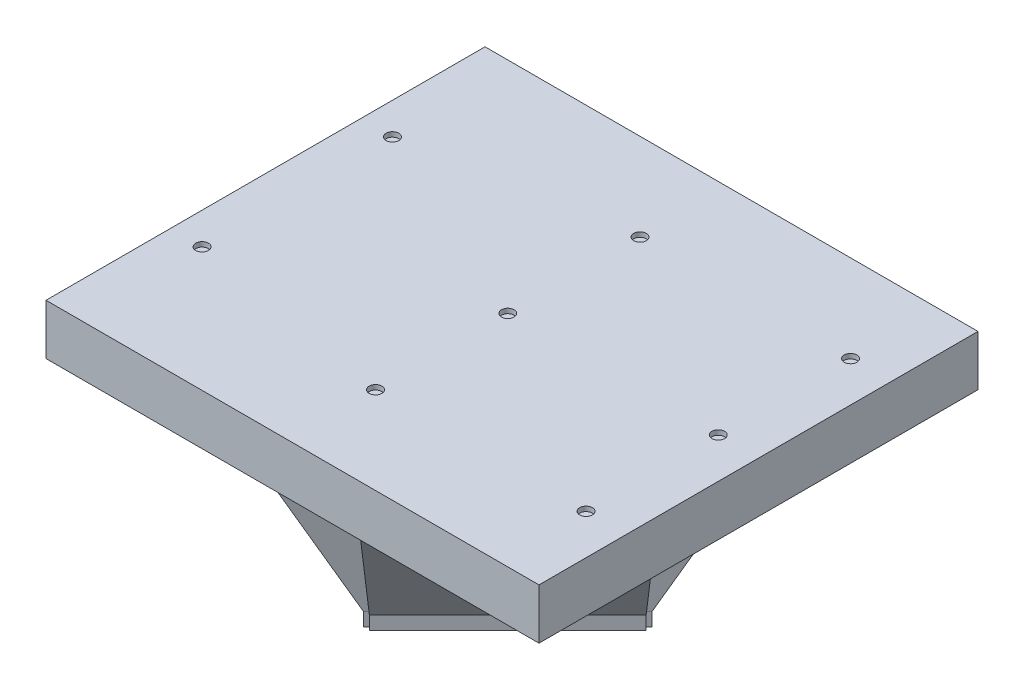
SolidWorks part; units mm, degrees
ref_plane "Front Plane" through (0, 0, 0) normal (0, 0, 1) x (1, 0, 0)
ref_plane "Top Plane" through (0, 0, 0) normal (0, 1, 0) x (1, 0, 0)
ref_plane "Right Plane" through (0, 0, 0) normal (1, 0, 0) x (0, 0, -1)
sketch "Sketch1" plane through (0, 0, 0) normal (0, 1, 0) x (1, 0, 0)
  line L1 (-46.6, 41.5) -> (46.6, 41.5)
  line L2 (-46.6, 41.5) -> (-46.6, -41.5)
  line L3 (-46.6, -41.5) -> (46.6, -41.5)
  line L4 (46.6, 41.5) -> (46.6, -41.5)
  line L5 (-46.6, 41.5) -> (46.6, -41.5) construction
  line L6 (-46.6, -41.5) -> (46.6, 41.5) construction
  point P0 (0, 0)
  dimension "D1" = 83
  dimension "D2" = 93.2
extrude "Boss-Extrude1" add sketch "Sketch1" against normal blind 9.55
sketch "Sketch2" plane through (0, -9.55, 0) normal (0, -1, 0) x (1, 0, 0)
  line L0 (-32.6387, 16.2823) -> (-17.0823, 31.8387) construction
  line L8 (-32.6387, 16.2823) -> (-17.0823, 31.8387) construction
  line L9 (-29.6334, 0.5492) -> (-37.942, 8.8577) construction
  line L10 (-29.6334, 0.5492) -> (-37.942, 8.8577) construction
  line L11 (-9.6577, 37.142) -> (-1.3492, 28.8334) construction
  line L12 (-9.6577, 37.142) -> (-1.3492, 28.8334) construction
  line L13 (15.4823, 31.8387) -> (31.0387, 16.2823) construction
  line L14 (15.4823, 31.8387) -> (31.0387, 16.2823) construction
  line L15 (-0.2508, 28.8334) -> (8.0577, 37.142) construction
  line L16 (-0.2508, 28.8334) -> (8.0577, 37.142) construction
  line L18 (36.342, 8.8577) -> (28.0334, 0.5492) construction
  line L19 (46.6, -41.5) -> (-46.6, 41.5) construction
  line L20 (36.342, 8.8577) -> (28.0334, 0.5492) construction
  line L21 (46.6, 41.5) -> (-46.6, -41.5) construction
  line L40 (31.0387, -16.2823) -> (15.4823, -31.8387) construction
  line L41 (31.0387, -16.2823) -> (15.4823, -31.8387) construction
  line L42 (28.0334, -0.5492) -> (36.342, -8.8577) construction
  line L43 (28.0334, -0.5492) -> (36.342, -8.8577) construction
  line L44 (8.0577, -37.142) -> (-0.2508, -28.8334) construction
  line L45 (8.0577, -37.142) -> (-0.2508, -28.8334) construction
  line L46 (-17.0823, -31.8387) -> (-32.6387, -16.2823) construction
  line L47 (-17.0823, -31.8387) -> (-32.6387, -16.2823) construction
  line L48 (-1.3492, -28.8334) -> (-9.6577, -37.142) construction
  line L49 (-1.3492, -28.8334) -> (-9.6577, -37.142) construction
  line L50 (-37.942, -8.8577) -> (-29.6334, -0.5492) construction
  line L51 (-37.942, -8.8577) -> (-29.6334, -0.5492) construction
  line L76 (-10.7183, -38.2026) -> (-0.8, -28.2843)
  line L77 (-0.8, -28.2843) -> (9.1183, -38.2026)
  line L78 (9.1183, -38.2026) -> (37.4026, -9.9183)
  line L79 (37.4026, -9.9183) -> (27.4843, 0)
  line L80 (27.4843, 0) -> (37.4026, 9.9183)
  line L81 (37.4026, 9.9183) -> (9.1183, 38.2026)
  line L82 (9.1183, 38.2026) -> (-0.8, 28.2843)
  line L83 (-0.8, 28.2843) -> (-10.7183, 38.2026)
  line L84 (-39.0026, 9.9183) -> (-10.7183, 38.2026)
  line L85 (-39.0026, 9.9183) -> (-29.0843, 0)
  line L86 (-29.0843, 0) -> (-39.0026, -9.9183)
  line L87 (-39.0026, -9.9183) -> (-10.7183, -38.2026)
ref_plane "Plane1" through (0, -35.75, 0) normal (0, -1, 0) x (-1, 0, 0)
sketch "Sketch3" plane through (0, -35.75, 0) normal (0, -1, 0) x (-1, 0, 0)
  line L0 (0.2508, 28.8334) -> (-28.0334, 0.5492) construction
  line L2 (1.3492, -28.8334) -> (29.6334, -0.5492) construction
  line L4 (-28.0334, -0.5492) -> (0.2508, -28.8334) construction
  line L5 (1.3492, 28.8334) -> (29.6334, 0.5492) construction
  line L6 (29.6334, -0.5492) -> (29.0843, 0) construction
  line L7 (29.0843, 0) -> (29.6334, 0.5492) construction
  line L8 (1.3492, 28.8334) -> (0.8, 28.2843) construction
  line L9 (0.8, 28.2843) -> (0.2508, 28.8334) construction
  line L10 (-28.0334, 0.5492) -> (-27.4843, 0) construction
  line L11 (-27.4843, 0) -> (-28.0334, -0.5492) construction
  line L12 (1.3492, -28.8334) -> (0.8, -28.2843) construction
  line L13 (0.8, -28.2843) -> (0.2508, -28.8334) construction
  line L14 (0.2508, 26.7121) -> (-25.9121, 0.5492)
  line L15 (-25.9121, 0.5492) -> (-25.363, 0)
  line L16 (-25.363, 0) -> (-25.9121, -0.5492)
  line L17 (-25.9121, -0.5492) -> (0.2508, -26.7121)
  line L18 (0.8, -26.163) -> (0.2508, -26.7121)
  line L19 (1.3492, -26.7121) -> (0.8, -26.163)
  line L20 (1.3492, -26.7121) -> (27.5121, -0.5492)
  line L21 (27.5121, -0.5492) -> (26.963, 0)
  line L22 (26.963, 0) -> (27.5121, 0.5492)
  line L23 (1.3492, 26.7121) -> (27.5121, 0.5492)
  line L24 (1.3492, 26.7121) -> (0.8, 26.163)
  line L25 (0.8, 26.163) -> (0.2508, 26.7121)
  dimension "D1" = 1.5
loft "Loft3" add profiles "Sketch3", "Sketch2"
sketch "Sketch5" plane through (0, -35.75, 0) normal (0, -1, 0) x (1, 0, 0)
  line L12 (-0.8, -26.163) -> (-0.2508, -26.7121)
  line L13 (-0.2508, -26.7121) -> (25.9121, -0.5492)
  line L14 (25.9121, -0.5492) -> (25.363, 0)
  line L15 (25.363, 0) -> (25.9121, 0.5492)
  line L16 (25.9121, 0.5492) -> (-0.2508, 26.7121)
  line L17 (-0.2508, 26.7121) -> (-0.8, 26.163)
  line L18 (-0.8, 26.163) -> (-1.3492, 26.7121)
  line L19 (-1.3492, 26.7121) -> (-27.5121, 0.5492)
  line L20 (-27.5121, 0.5492) -> (-26.963, 0)
  line L21 (-26.963, 0) -> (-27.5121, -0.5492)
  line L22 (-27.5121, -0.5492) -> (-1.3492, -26.7121)
  line L23 (-1.3492, -26.7121) -> (-0.8, -26.163)
  line L24 (-0.8, -26.163) -> (-0.2508, -26.7121)
  line L25 (-0.2508, -26.7121) -> (25.9121, -0.5492)
  line L26 (25.9121, -0.5492) -> (25.363, 0)
  line L27 (25.363, 0) -> (25.9121, 0.5492)
  line L28 (25.9121, 0.5492) -> (-0.2508, 26.7121)
  line L29 (-0.2508, 26.7121) -> (-0.8, 26.163)
  line L30 (-0.8, 26.163) -> (-1.3492, 26.7121)
  line L31 (-1.3492, 26.7121) -> (-27.5121, 0.5492)
  line L32 (-27.5121, 0.5492) -> (-26.963, 0)
  line L33 (-26.963, 0) -> (-27.5121, -0.5492)
  line L34 (-27.5121, -0.5492) -> (-1.3492, -26.7121)
  line L35 (-1.3492, -26.7121) -> (-0.8, -26.163)
  dimension "D1" = 0
extrude "Boss-Extrude3" add sketch "Sketch5" along normal blind 2.5
sketch "Sketch6" plane through (0, 0, 0) normal (0, 1, 0) x (1, 0, 0)
  line L35 (-40.6, -14.9978) -> (-38, -16.4989)
  line L36 (-42.1, -15.8638) -> (-40.6, -14.9978)
  line L37 (-42.1, 15.8638) -> (-42.1, -15.8638)
  line L38 (-40.6, 14.9978) -> (-42.1, 15.8638)
  line L39 (-38, 16.4989) -> (-40.6, 14.9978)
  line L40 (-38, 19.5011) -> (-38, 16.4989)
  line L41 (-40.6, 21.0022) -> (-38, 19.5011)
  line L42 (-42.1, 20.1362) -> (-40.6, 21.0022)
  line L43 (-42.1, 31) -> (-42.1, 20.1362)
  line L44 (40.5, 31) -> (-42.1, 31)
  line L45 (40.5, 27.1362) -> (40.5, 31)
  line L46 (39, 28.0022) -> (40.5, 27.1362)
  line L47 (36.4, 26.5011) -> (39, 28.0022)
  line L48 (36.4, 23.4989) -> (36.4, 26.5011)
  line L49 (39, 21.9978) -> (36.4, 23.4989)
  line L50 (40.5, 22.8638) -> (39, 21.9978)
  line L51 (40.5, 2.1362) -> (40.5, 22.8638)
  line L52 (39, 3.0022) -> (40.5, 2.1362)
  line L53 (36.4, 1.5011) -> (39, 3.0022)
  line L54 (36.4, -1.5011) -> (36.4, 1.5011)
  line L55 (39, -3.0022) -> (36.4, -1.5011)
  line L56 (40.5, -2.1362) -> (39, -3.0022)
  line L57 (40.5, -22.8638) -> (40.5, -2.1362)
  line L58 (39, -21.9978) -> (40.5, -22.8638)
  line L59 (36.4, -23.4989) -> (39, -21.9978)
  line L60 (36.4, -26.5011) -> (36.4, -23.4989)
  line L61 (39, -28.0022) -> (36.4, -26.5011)
  line L62 (40.5, -27.1362) -> (39, -28.0022)
  line L63 (40.5, -31) -> (40.5, -27.1362)
  line L64 (-42.1, -31) -> (40.5, -31)
  line L65 (-42.1, -20.1362) -> (-42.1, -31)
  line L66 (-40.6, -21.0022) -> (-42.1, -20.1362)
  line L67 (-38, -19.5011) -> (-40.6, -21.0022)
  line L68 (-38, -16.4989) -> (-38, -19.5011)
  line L69 (-40.6, -14.9978) -> (-38, -16.4989)
  line L70 (-42.1, -15.8638) -> (-40.6, -14.9978)
  line L71 (-42.1, 15.8638) -> (-42.1, -15.8638)
  line L72 (-40.6, 14.9978) -> (-42.1, 15.8638)
  line L73 (-38, 16.4989) -> (-40.6, 14.9978)
  line L74 (-38, 19.5011) -> (-38, 16.4989)
  line L75 (-40.6, 21.0022) -> (-38, 19.5011)
  line L76 (-42.1, 20.1362) -> (-40.6, 21.0022)
  line L77 (-42.1, 31) -> (-42.1, 20.1362)
  line L78 (40.5, 31) -> (-42.1, 31)
  line L79 (40.5, 27.1362) -> (40.5, 31)
  line L80 (39, 28.0022) -> (40.5, 27.1362)
  line L81 (36.4, 26.5011) -> (39, 28.0022)
  line L82 (36.4, 23.4989) -> (36.4, 26.5011)
  line L83 (39, 21.9978) -> (36.4, 23.4989)
  line L84 (40.5, 22.8638) -> (39, 21.9978)
  line L85 (40.5, 2.1362) -> (40.5, 22.8638)
  line L86 (39, 3.0022) -> (40.5, 2.1362)
  line L87 (36.4, 1.5011) -> (39, 3.0022)
  line L88 (36.4, -1.5011) -> (36.4, 1.5011)
  line L89 (39, -3.0022) -> (36.4, -1.5011)
  line L90 (40.5, -2.1362) -> (39, -3.0022)
  line L91 (40.5, -22.8638) -> (40.5, -2.1362)
  line L92 (39, -21.9978) -> (40.5, -22.8638)
  line L93 (36.4, -23.4989) -> (39, -21.9978)
  line L94 (36.4, -26.5011) -> (36.4, -23.4989)
  line L95 (39, -28.0022) -> (36.4, -26.5011)
  line L96 (40.5, -27.1362) -> (39, -28.0022)
  line L97 (40.5, -31) -> (40.5, -27.1362)
  line L98 (-42.1, -31) -> (40.5, -31)
  line L99 (-42.1, -20.1362) -> (-42.1, -31)
  line L100 (-40.6, -21.0022) -> (-42.1, -20.1362)
  line L101 (-38, -19.5011) -> (-40.6, -21.0022)
  line L102 (-38, -16.4989) -> (-38, -19.5011)
  circle A0 centre (-0.8, -25) radius 0.4862 construction
  circle A1 centre (-0.8, -25) radius 0.4862 construction
  circle A2 centre (-0.8, 0) radius 0.4862 construction
  circle A3 centre (-0.8, 0) radius 0.4862 construction
  circle A4 centre (-40.6, -18) radius 0.4862 construction
  circle A5 centre (-40.6, -18) radius 0.4862 construction
  circle A6 centre (-40.6, 18) radius 0.4862 construction
  circle A7 centre (-40.6, 18) radius 0.4862 construction
  circle A8 centre (39, 25) radius 0.4862 construction
  circle A9 centre (39, 25) radius 0.4862 construction
  circle A10 centre (39, 0) radius 0.4862 construction
  circle A11 centre (39, 0) radius 0.4862 construction
  circle A12 centre (39, -25) radius 0.4862 construction
  circle A13 centre (39, -25) radius 0.4862 construction
  circle A14 centre (-0.8, 25) radius 0.4862 construction
  circle A15 centre (-0.8, 25) radius 0.4862 construction
  circle A16 centre (39, -25) radius 1.2
  circle A17 centre (39, 0) radius 1.2
  circle A18 centre (39, 25) radius 1.2
  circle A19 centre (-40.6, 18) radius 1.2
  circle A20 centre (-40.6, -18) radius 1.2
  circle A21 centre (-0.8, -25) radius 1.2
  circle A22 centre (-0.8, 0) radius 1.2
  circle A23 centre (-0.8, 25) radius 1.2
  dimension "D2" = 2.4
  dimension "D1" = 0
extrude "Cut-Extrude1" cut sketch "Sketch6" against normal blind 0.9 contours A16 | A17 | A21 | A22 | A18 | A23 | A19 | A20 | L69 L102 L101 L100 L99 L98 L97 L96 L95 L94 L93 L92 L91 L90 L89 L88 L87 L86 L85 L84 L83 L82 L81 L80 L79 L78 L77 L76 L75 L74 L73 L72 L71 L70
